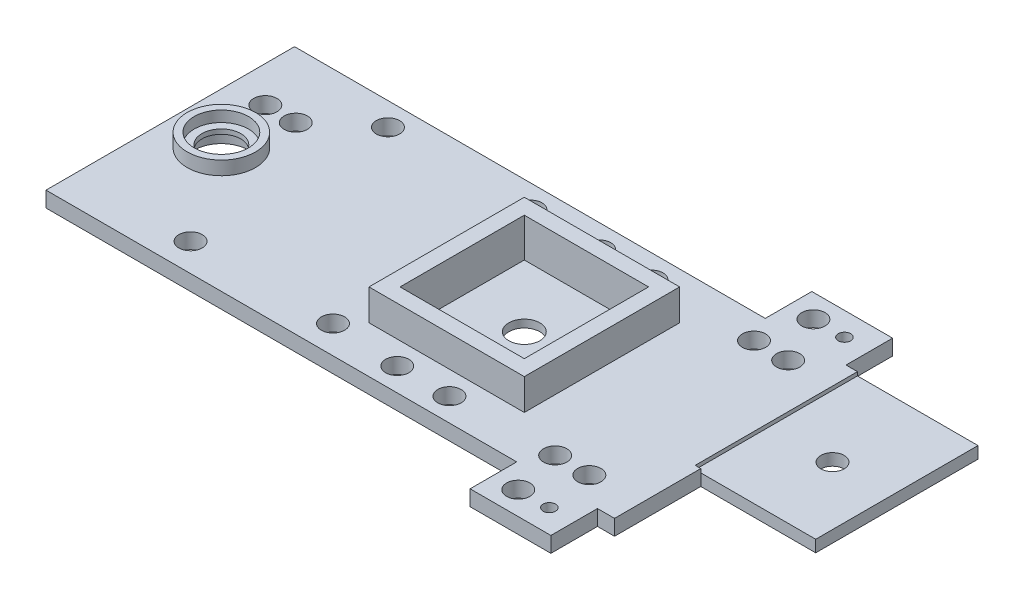
SolidWorks part; units mm, degrees
ref_plane "Front Plane" through (0, 0, 0) normal (0, 0, 1) x (1, 0, 0)
ref_plane "Top Plane" through (0, 0, 0) normal (0, 1, 0) x (1, 0, 0)
ref_plane "Right Plane" through (0, 0, 0) normal (1, 0, 0) x (0, 0, -1)
sketch "Sketch1" plane through (0, 0, 0) normal (0, 1, 0) x (1, 0, 0)
  line L1 (-279.4, -50.8) -> (0, -50.8)
  line L2 (-279.4, -50.8) -> (-279.4, 50.8)
  line L3 (-279.4, 50.8) -> (0, 50.8)
  line L4 (0, -50.8) -> (0, 50.8)
  point P0 (0, 0)
  dimension "D1" = 279.4
  dimension "D2" = 101.6
  dimension "D3" = 50.8
extrude "Boss-Extrude1" add sketch "Sketch1" along normal blind 6.35
sketch "Sketch2" plane through (0, 6.35, 0) normal (0, 1, 0) x (1, 0, 0)
  line L0 (-279.4, 50.8) -> (-279.4, -50.8) construction
  line L2 (0, 50.8) -> (-279.4, 50.8) construction
  circle A0 centre (-258.5106, 0) radius 13.97
  dimension "D1" = 50.8
  dimension "D2" = 27.94
  dimension "D3" = 20.8894
extrude "Boss-Extrude3" add sketch "Sketch2" along normal blind 5.5562
sketch "Sketch9" plane through (0, 11.9062, 0) normal (0, 1, 0) x (1, 0, 0)
  circle A0 centre (-258.5106, 0) radius 11.1125
  dimension "D1" = 22.225
extrude "Cut-Extrude4" cut sketch "Sketch9" against normal blind 4.445
sketch "Sketch10" plane through (0, 0, 0) normal (0, -1, 0) x (-1, 0, 0)
  circle A0 centre (258.5106, 0) radius 11.1125
  dimension "D1" = 22.225
extrude "Cut-Extrude5" cut sketch "Sketch10" against normal blind 5.5562
sketch "Sketch11" plane through (0, 7.4613, 0) normal (0, 1, 0) x (1, 0, 0)
  circle A0 centre (-258.5106, 0) radius 7.9375
  dimension "D1" = 15.875
extrude "Cut-Extrude6" cut sketch "Sketch11" against normal through all
sketch "Sketch12" plane through (0, 6.35, 0) normal (0, 1, 0) x (1, 0, 0)
  line L0 (0, 50.8) -> (-279.4, 50.8) construction
  line L1 (-279.4, 50.8) -> (-279.4, -50.8) construction
  circle A0 centre (-134.6662, 0) radius 6.35
  dimension "D1" = 12.7
  dimension "D2" = 50.8
  dimension "D3" = 144.7338
extrude "Cut-Extrude7" cut sketch "Sketch12" against normal through all
sketch "Sketch22" plane through (0, 6.35, 0) normal (0, 1, 0) x (1, 0, 0)
  line L1 (-102.9162, -31.75) -> (-166.4162, -31.75)
  line L2 (-102.9162, -31.75) -> (-102.9162, 31.75)
  line L3 (-102.9162, 31.75) -> (-166.4162, 31.75)
  line L4 (-166.4162, -31.75) -> (-166.4162, 31.75)
  line L5 (-102.9162, -31.75) -> (-166.4162, 31.75) construction
  line L6 (-102.9162, 31.75) -> (-166.4162, -31.75) construction
  circle A0 centre (-134.6662, 0) radius 6.35 construction
  point P0 (-134.6662, 0)
  dimension "D1" = 63.5
  dimension "D2" = 63.5
extrude "Boss-Extrude7" add sketch "Sketch22" along normal blind 12.7
sketch "Sketch25" plane through (0, 19.05, 0) normal (0, 1, 0) x (1, 0, 0)
  line L1 (-109.2662, -25.4) -> (-160.0662, -25.4)
  line L2 (-109.2662, -25.4) -> (-109.2662, 25.4)
  line L3 (-109.2662, 25.4) -> (-160.0662, 25.4)
  line L4 (-160.0662, -25.4) -> (-160.0662, 25.4)
  line L5 (-109.2662, -25.4) -> (-160.0662, 25.4) construction
  line L6 (-109.2662, 25.4) -> (-160.0662, -25.4) construction
  circle A0 centre (-134.6662, 0) radius 6.35 construction
  point P0 (-134.6662, 0)
  dimension "D1" = 50.8
  dimension "D2" = 50.8
extrude "Cut-Extrude11" cut sketch "Sketch25" against normal blind 15.875
sketch "Sketch32" plane through (0, 6.35, 0) normal (0, 1, 0) x (1, 0, 0)
  line L0 (0, -50.8) -> (0, 50.8) construction
  line L3 (-279.4, -50.8) -> (0, -50.8) construction
  line L5 (0, 50.8) -> (-279.4, 50.8) construction
  circle A0 centre (-67.442, -40.64) radius 4.7625
  circle A1 centre (-81.412, -40.64) radius 4.7625
  circle A2 centre (-67.442, 40.64) radius 4.7625
  circle A3 centre (-81.412, 40.64) radius 4.7625
  dimension "D1" = 10.16
  dimension "D2" = 10.16
  dimension "D3" = 10.16
  dimension "D4" = 10.16
  dimension "D9" = 9.525
  dimension "D10" = 9.525
  dimension "D11" = 9.525
  dimension "D12" = 9.525
  dimension "D5" = 13.97
  dimension "D6" = 13.97
  dimension "D7" = 81.28
  dimension "D8" = 81.412
extrude "Cut-Extrude12" cut sketch "Sketch32" against normal blind 6.35
sketch "Sketch38" plane through (0, 6.35, 0) normal (0, 1, 0) x (1, 0, 0)
  line L0 (0, -50.8) -> (0, 50.8) construction
  line L1 (0, -34.0128) -> (-46.99, -34.0128)
  line L2 (0, -34.0128) -> (0, -15.5426)
  line L3 (0, -15.5426) -> (-46.99, -15.5426)
  line L4 (-46.99, -34.0128) -> (-46.99, -15.5426)
  line L6 (-279.4, -50.8) -> (0, -50.8) construction
  dimension "D1" = 35.2574
  dimension "D2" = 18.4703
  dimension "D3" = 46.99
extrude "Cut-Extrude13" cut sketch "Sketch38" against normal blind 6.35
sketch "Sketch60" plane through (0, 6.35, 0) normal (0, 1, 0) x (1, 0, 0)
  line L1 (-279.4, 50.8) -> (-279.4, -50.8) construction
  line L2 (0, 50.8) -> (-279.4, 50.8) construction
  circle A0 centre (-231.7492, 41.3241) radius 4.7625
  circle A1 centre (-231.7492, -39.3693) radius 4.7625
  circle A2 centre (-173.5092, -39.3693) radius 4.7625
  circle A3 centre (-173.5092, 41.3241) radius 4.7625
  dimension "D1" = 47.6508
  dimension "D5" = 9.525
  dimension "D6" = 9.525
  dimension "D7" = 9.525
  dimension "D8" = 9.525
  dimension "D2" = 58.24
  dimension "D3" = 80.6935
  dimension "D4" = 9.4759
  dimension "D9" = 105.8908
extrude "Cut-Extrude23" cut sketch "Sketch60" against normal up to surface (6.35 mm away) up to face at (-81.5975, 0, 12.3889)
sketch "Sketch64" plane through (0, 6.35, 0) normal (0, 1, 0) x (1, 0, 0)
  line L0 (-279.4, -50.8) -> (0, -50.8) construction
  circle A0 centre (-145.3342, -41.275) radius 4.7625
  circle A1 centre (-123.9982, -41.275) radius 4.7625
  circle A3 centre (-134.6662, 0) radius 6.35 construction
  dimension "D1" = 21.336
  dimension "D3" = 9.525
  dimension "D4" = 9.525
  dimension "D2" = 10.668
  dimension "D5" = 9.525
  dimension "D6" = 9.525
extrude "Cut-Extrude24" cut sketch "Sketch64" against normal through all
mirror "Mirror1" about plane through (0, 0, 0) normal (0, 0, 1) of "Cut-Extrude24"
sketch "Sketch69" plane through (0, 0, 50.8) normal (0, 0, 1) x (1, 0, 0)
  line L0 (-279.4, 6.35) -> (0, 6.35) construction
  line L1 (-86.9754, 6.35) -> (-53.9554, 6.35)
  line L2 (-86.9754, 6.35) -> (-86.9754, 0)
  line L3 (-86.9754, 0) -> (-53.9554, 0)
  line L4 (-53.9554, 6.35) -> (-53.9554, 0)
  line L5 (-279.4, 0) -> (0, 0) construction
  line L7 (0, 6.35) -> (0, 0) construction
  dimension "D1" = 33.02
  dimension "D2" = 53.9554
extrude "Boss-Extrude10" add sketch "Sketch69" along normal blind 19.05
sketch "Sketch70" plane through (0, 6.35, 0) normal (0, 1, 0) x (1, 0, 0)
  line L1 (-86.9754, -69.85) -> (-86.9754, -50.8) construction
  circle A0 centre (-76.8154, -60.325) radius 4.7625
  circle A1 centre (-64.1154, -60.325) radius 2.54
  point P6 (-86.9754, -60.325)
  dimension "D1" = 9.525
  dimension "D3" = 5.08
  dimension "D2" = 10.16
  dimension "D4" = 22.86
extrude "Cut-Extrude26" cut sketch "Sketch70" against normal up to surface (6.35 mm away) up to face at (-145.3342, 0, -46.0375)
mirror "Mirror2" about plane through (0, 0, 0) normal (0, 0, 1) of "Cut-Extrude26", "Boss-Extrude10"
sketch "Sketch76" plane through (0, 6.35, 0) normal (0, 1, 0) x (1, 0, 0)
  line L0 (-279.4, 50.8) -> (-279.4, -50.8) construction
  line L1 (-86.9754, 50.8) -> (-279.4, 50.8) construction
  circle A0 centre (-264.668, 24.13) radius 4.7625
  circle A1 centre (-252.222, 24.13) radius 4.7625
  dimension "D1" = 14.732
  dimension "D2" = 12.446
  dimension "D3" = 9.525
  dimension "D4" = 9.525
  dimension "D5" = 26.67
  dimension "D6" = 26.67
extrude "Cut-Extrude29" cut sketch "Sketch76" against normal up to surface (6.35 mm away) up to face at (-76.8154, 0, -65.0875)
sketch "Sketch77" plane through (0, 6.35, 0) normal (0, 1, 0) x (1, 0, 0)
  line L0 (-53.9554, -50.8) -> (0, -50.8) construction
  line L1 (0, -34.0128) -> (-46.99, -34.0128)
  line L2 (0, -34.0128) -> (0, -50.8)
  line L3 (0, -50.8) -> (-46.99, -50.8)
  line L4 (-46.99, -34.0128) -> (-46.99, -50.8)
  line L5 (-46.99, -15.5426) -> (-46.99, -34.0128) construction
extrude "Cut-Extrude30" cut sketch "Sketch77" against normal up to surface (6.35 mm away) up to face at (-264.668, 0, -28.8925)
sketch "Sketch78" plane through (0, 6.35, 0) normal (0, 1, 0) x (1, 0, 0)
  line L0 (0, -15.5426) -> (-46.99, -15.5426) construction
  line L1 (-49.276, -15.5426) -> (0, -15.5426)
  line L2 (-49.276, -15.5426) -> (-49.276, 50.8)
  line L3 (-49.276, 50.8) -> (0, 50.8)
  line L4 (0, -15.5426) -> (0, 50.8)
  dimension "D1" = 49.276
extrude "Cut-Extrude32" cut sketch "Sketch78" against normal blind 1.524 contours L2 L1 L4 L3
sketch "Sketch79" plane through (0, 4.826, 0) normal (0, 1, 0) x (1, 0, 0)
  line L0 (-46.99, -15.5426) -> (0, -15.5426) construction
  line L1 (0, -15.5426) -> (0, 50.8) construction
  circle A0 centre (-23.876, 15.1914) radius 4.7625
  dimension "D3" = 9.525
  dimension "D1" = 30.734
  dimension "D2" = 23.876
extrude "Cut-Extrude33" cut sketch "Sketch79" against normal up to surface (4.826 mm away) up to face at (-86.8931, 0, 2.2204)
